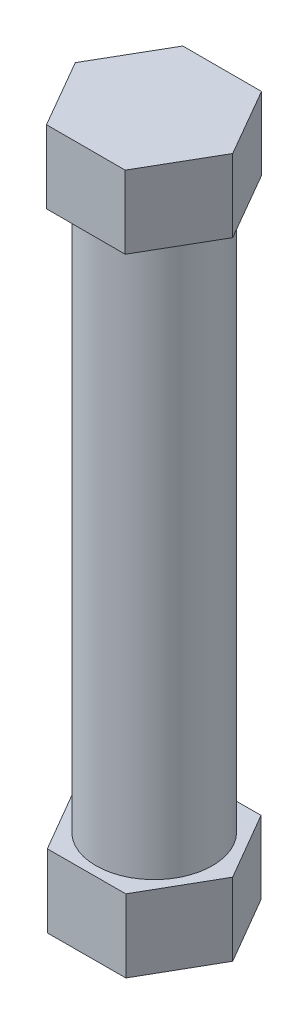
SolidWorks part; units mm, degrees
material "6061 Alloy"
ref_plane "Front Plane" through (0, 0, 0) normal (0, 0, 1) x (1, 0, 0)
ref_plane "Top Plane" through (0, 0, 0) normal (0, 1, 0) x (1, 0, 0)
ref_plane "Right Plane" through (0, 0, 0) normal (1, 0, 0) x (0, 0, -1)
sketch "Sketch1" plane through (0, 0, 0) normal (0, 1, 0) x (1, 0, 0)
  circle A0 centre (0, 0) radius 4
extrude "Boss-Extrude1" add sketch "Sketch1" along normal blind 38
sketch "Sketch2" plane through (0, 38, 0) normal (0, 1, 0) x (1, 0, 0)
  line L1 (5.3719, 0.0162) -> (2.6719, 4.6928)
  line L2 (2.6719, 4.6928) -> (-2.7281, 4.6928)
  line L3 (-2.7281, 4.6928) -> (-5.4281, 0.0162)
  line L4 (-5.4281, 0.0162) -> (-2.7281, -4.6603)
  line L5 (-2.7281, -4.6603) -> (2.6719, -4.6603)
  line L6 (2.6719, -4.6603) -> (5.3719, 0.0162)
  circle A0 centre (-0.0281, 0.0162) radius 4.6765 construction
  dimension "D1" = 5.4
extrude "Boss-Extrude2" add sketch "Sketch2" along normal blind 5
sketch "Sketch3" plane through (0, 0, 0) normal (0, -1, 0) x (1, 0, 0)
  line L1 (5.3719, -0.0162) -> (2.7, 4.6441)
  line L2 (2.7, 4.6441) -> (-2.6719, 4.6603)
  line L3 (-2.6719, 4.6603) -> (-5.3719, 0.0162)
  line L4 (-5.3719, 0.0162) -> (-2.7, -4.6441)
  line L5 (-2.7, -4.6441) -> (2.6719, -4.6603)
  line L6 (2.6719, -4.6603) -> (5.3719, -0.0162)
  circle A0 centre (0, 0) radius 4.6522 construction
extrude "Boss-Extrude3" add sketch "Sketch3" along normal blind 5
